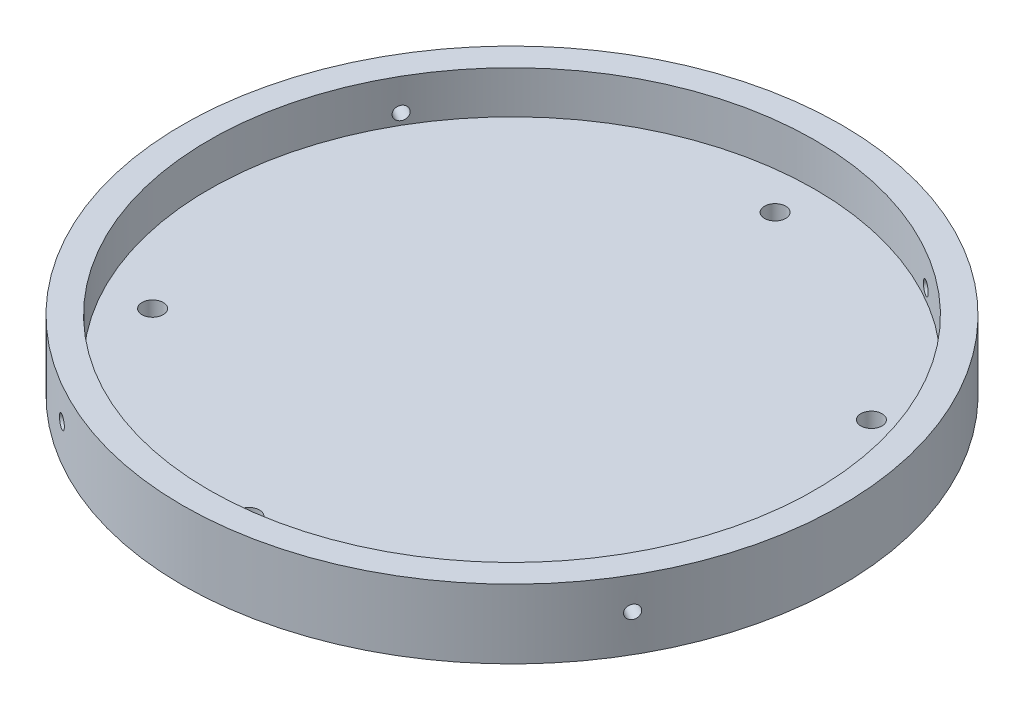
SolidWorks part; units mm, degrees
ref_plane "Front Plane" through (0, 0, 0) normal (0, 0, 1) x (1, 0, 0)
ref_plane "Top Plane" through (0, 0, 0) normal (0, 1, 0) x (1, 0, 0)
ref_plane "Right Plane" through (0, 0, 0) normal (1, 0, 0) x (0, 0, -1)
sketch "Sketch1" plane through (0, 0, 0) normal (0, 1, 0) x (1, 0, 0)
  circle A0 centre (0, 0) radius 62
  dimension "D1" = 124
extrude "Boss-Extrude1" add sketch "Sketch1" along normal blind 5
sketch "Sketch2" plane through (0, 5, 0) normal (0, 1, 0) x (1, 0, 0)
  circle A0 centre (0, 49.5) radius 2
  dimension "D2" = 4
  dimension "D1" = 49.5
extrude "Cut-Extrude1" cut sketch "Sketch2" against normal blind 5 contours A0
pattern_circular "CirPattern1" count 2 every 120 about axis through (0, 5, 0) along (0, 1, 0) of "Cut-Extrude1"
sketch "Sketch4" plane through (0, 5, 0) normal (0, 1, 0) x (1, 0, 0)
  line L0 (0, 49.5) -> (-42.8683, -24.75) construction
  line L1 (0, 0) -> (-23.6703, -40.9981) construction
ref_plane "Plane1" through (0, 0, 0) normal (-0.866, 0, -0.5) x (-0.5, 0, 0.866)
mirror "Mirror1" about plane through (0, 0, 0) normal (-0.866, 0, -0.5) of "Cut-Extrude1", "CirPattern1"
sketch "Sketch5" plane through (0, 5, 0) normal (0, 1, 0) x (1, 0, 0)
  circle A0 centre (0, 0) radius 62
  circle A1 centre (0, 0) radius 57
  dimension "D1" = 5
extrude "Boss-Extrude2" add sketch "Sketch5" along normal blind 8
sketch "Sketch6" plane through (0, 0, 0) normal (-0.866, 0, -0.5) x (-0.5, 0, 0.866)
  line L0 (57, 13) -> (-57, 13) construction
  circle A0 centre (0, 7) radius 1.25
  dimension "D1" = 2.5
  dimension "D2" = 6
extrude "Cut-Extrude2" cut sketch "Sketch6" against normal blind 90 and the other way blind 102 contours A0
pattern_circular "CirPattern2" count 2 every 90 about axis through (0, 13, 0) along (0, 1, 0) of "Cut-Extrude2"
